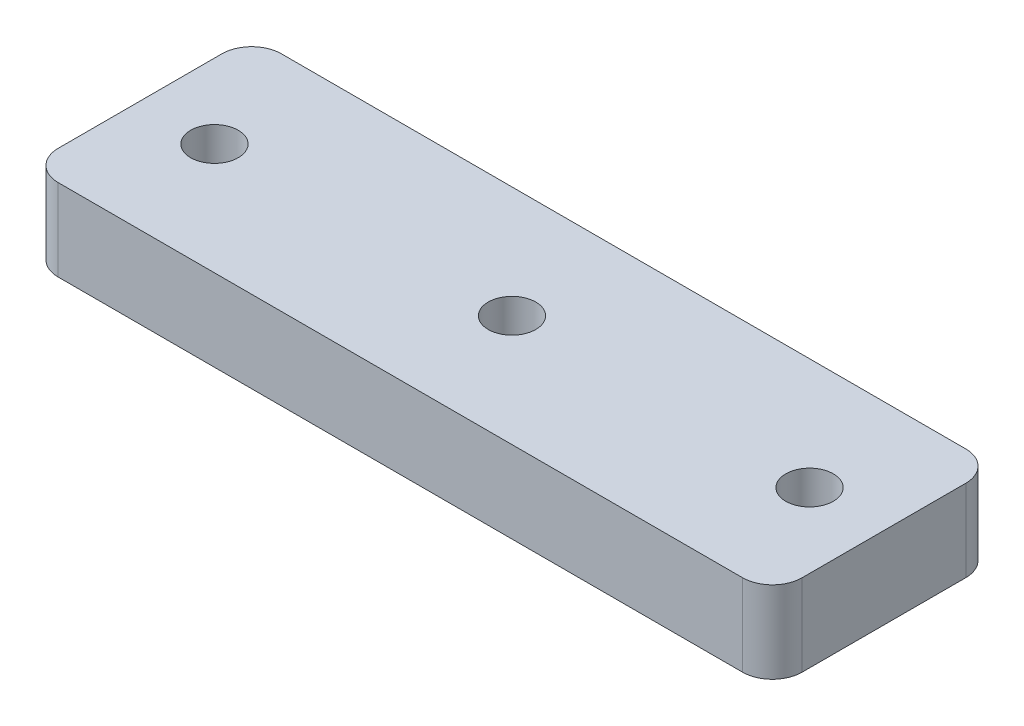
SolidWorks part; units mm, degrees
ref_plane "前视基准面" through (0, 0, 0) normal (0, 0, 1) x (1, 0, 0)
ref_plane "上视基准面" through (0, 0, 0) normal (0, 1, 0) x (1, 0, 0)
ref_plane "右视基准面" through (0, 0, 0) normal (1, 0, 0) x (0, 0, -1)
other "Configuration Table"
sketch "草图1" plane through (0, 0, 0) normal (0, 1, 0) x (1, 0, 0)
  line L0 (-25, 0) -> (25, 0) construction
  line L1 (-25, -7.5) -> (25, -7.5)
  line L2 (-25, -7.5) -> (-25, 7.5)
  line L3 (-25, 7.5) -> (25, 7.5)
  line L4 (25, -7.5) -> (25, 7.5)
  line L5 (-25, -7.5) -> (25, 7.5) construction
  line L6 (-25, 7.5) -> (25, -7.5) construction
  circle A0 centre (-20, 0) radius 1.6
  circle A1 centre (0, 0) radius 1.6
  circle A2 centre (20, 0) radius 1.6
  point P0 (0, 0)
  dimension "D3" = 3.2
  dimension "D4" = 3.2
  dimension "D5" = 3.2
  dimension "D6" = 20
  dimension "D7" = 20
  dimension "D1" = 15
  dimension "D2" = 50
extrude "凸台-拉伸1" add sketch "草图1" along normal blind 5.5
fillet "圆角1" radius 2 4 edges at (-25, 2.75, 7.5) (-25, 2.75, -7.5) (25, 2.75, -7.5) (25, 2.75, 7.5)
